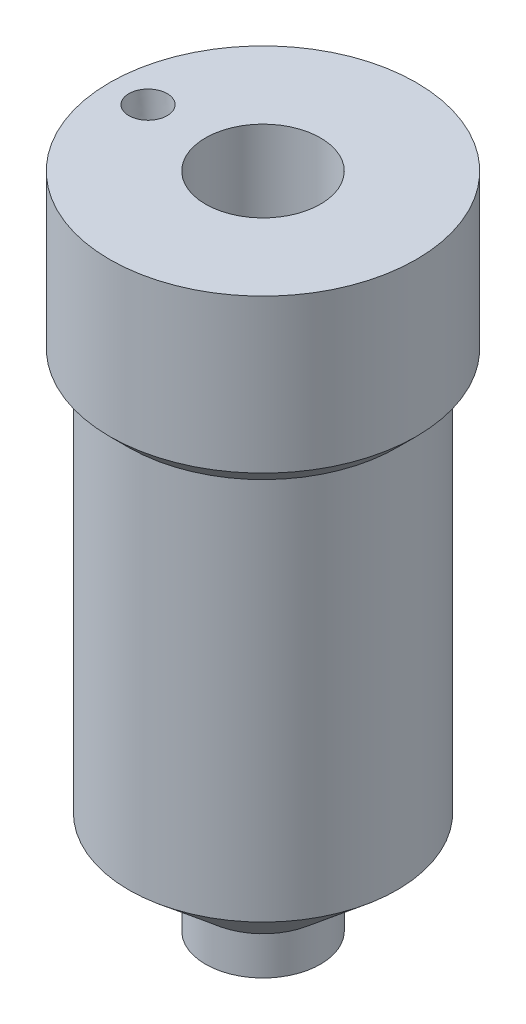
SolidWorks part; units mm, degrees
material "Brass"
ref_plane "Front Plane" through (0, 0, 0) normal (0, 0, 1) x (1, 0, 0)
ref_plane "Top Plane" through (0, 0, 0) normal (0, 1, 0) x (1, 0, 0)
ref_plane "Right Plane" through (0, 0, 0) normal (1, 0, 0) x (0, 0, -1)
sketch "Sketch1" plane through (0, 0, 0) normal (0, 0, 1) x (1, 0, 0)
  line L0 (0, 26.5455) -> (0, -14.7683) construction
  line L1 (3, -1.9686) -> (3, 21.0314)
  line L2 (3, 21.0314) -> (8, 21.0314)
  line L3 (8, 21.0314) -> (8, 13.0314)
  line L4 (8, 13.0314) -> (7, 12.0314)
  line L5 (7, 12.0314) -> (7, -7.9686)
  line L6 (7, -7.9686) -> (3, -11.325)
  line L7 (3, -11.325) -> (3, -13.325)
  line L8 (3, -13.325) -> (0.5, -14.7683)
  line L9 (0.5, -14.7683) -> (0.5, -9.8683)
  line L10 (3, -1.9686) -> (4.9948, -1.9686) construction
  line L11 (0.5, -9.0404) -> (3.9104, -5.6301) construction
  arc A0 (1.0858, -8.4541) -> (0.5, -9.8683) centre (2.5, -9.8683) ccw
  spline S0 degree 3 poles (1.0858, -8.4541) (5.8006, -3.7393) (7.5492, -1.9686) (3, -1.9686) knots 0.037994 0.037994 0.037994 0.037994 1 1 1 1
  point P17 (3, -1.9686)
  dimension "D9" = 2
  dimension "D17" = 13.6475
  dimension "D18" = 20.0031
  dimension "D1" = 8
  dimension "D2" = 3
  dimension "D3" = 7
  dimension "D4" = 0.5
  dimension "D5" = 29
  dimension "D6" = 23
  dimension "D7" = 20
  dimension "D8" = 1
  dimension "D10" = 50
  dimension "D11" = 60
  dimension "D12" = 45
  dimension "D13" = 4.9
  dimension "D14" = 2
  dimension "D15" = 2.5
  dimension "D16" = 14.7683
revolve "Revolve1" add sketch "Sketch1" angle 360 about L0
sketch "Sketch2" plane through (0, 0, 0) normal (0, 0, 1) x (1, 0, 0)
  line L0 (-6, 21.0314) -> (-4.6, -2.9719)
  line L1 (8, 21.0314) -> (-8, 21.0314) construction
  line L2 (3, 21.0314) -> (-3, 21.0314) construction
  point P4 (0, 21.0314)
  dimension "D1" = 6
  dimension "D2" = 24.0034
  dimension "D3" = 4.6
sketch "Sketch3" plane through (0, 21.0314, 0) normal (0, 1, 0) x (1, 0, 0)
  circle A0 centre (-6, 0) radius 1
  dimension "D1" = 2
sweep "Cut-Sweep1" cut profiles "Sketch3" path "Sketch2"
sketch "Sketch4" plane through (0, 0, 0) normal (0, 0, 1) x (1, 0, 0)
  line L0 (0.5, -14.7683) -> (-0.5, -14.7683) construction
  line L1 (0.4, -14.7683) -> (0.5, -14.6683)
  line L2 (0, -14.7683) -> (0.4, -14.7683)
  line L3 (0, -15.1683) -> (0, -15.2683)
  line L4 (0.5, -14.6683) -> (0.5, -14.7683)
  line L5 (0, -14.7683) -> (0, -15.3947) construction
  arc A0 (0, -15.2683) -> (0.5, -14.7683) centre (0, -14.7683) ccw
  arc A1 (0, -15.1683) -> (0.4, -14.7683) centre (0, -14.7683) ccw
  dimension "D1" = 1
  dimension "D2" = 0.8
  dimension "D3" = 0.1
  dimension "D4" = 0.1
revolve "Revolve2" add sketch "Sketch4" angle 360 about L5
sketch "Sketch5" plane through (0, 0, 0) normal (0, 0, 1) x (1, 0, 0)
  line L0 (0, -15.1183) -> (0, -15.4683)
  line L1 (0, -15.4683) -> (0.07, -15.4683)
  line L2 (0.07, -15.4683) -> (0.07, -15.1183)
  line L3 (0.07, -15.1183) -> (0, -15.1183)
  line L4 (0.4, -14.7683) -> (-0.4, -14.7683) construction
  line L5 (-0.1519, -15.0837) -> (-0.3037, -15.399)
  line L6 (-0.0888, -15.114) -> (-0.1519, -15.0837)
  line L7 (-0.2407, -15.4294) -> (-0.0888, -15.114)
  line L8 (-0.3037, -15.399) -> (-0.2407, -15.4294)
  line L9 (-0.2736, -14.9866) -> (-0.5473, -15.2048)
  line L10 (-0.23, -15.0413) -> (-0.2736, -14.9866)
  line L11 (-0.5036, -15.2595) -> (-0.23, -15.0413)
  line L12 (-0.5473, -15.2048) -> (-0.5036, -15.2595)
  line L13 (-0.3412, -14.8462) -> (-0.6824, -14.9241)
  line L14 (-0.3256, -14.9145) -> (-0.3412, -14.8462)
  line L15 (-0.6669, -14.9923) -> (-0.3256, -14.9145)
  line L16 (-0.6824, -14.9241) -> (-0.6669, -14.9923)
  line L57 (-0.698, -14.6808) -> (-0.3568, -14.7587) [skipped]
  line L58 (-0.3412, -14.6904) -> (-0.6824, -14.6126) [skipped]
  line L59 (-0.5909, -14.3866) -> (-0.3173, -14.6048) [skipped]
  line L60 (-0.2736, -14.5501) -> (-0.5473, -14.3319) [skipped]
  line L61 (-0.3668, -14.168) -> (-0.2149, -14.4834) [skipped]
  line L62 (-0.1519, -14.453) -> (-0.3037, -14.1377) [skipped]
  line L63 (-0.07, -14.0683) -> (-0.07, -14.4183) [skipped]
  line L64 (0, -14.4183) -> (0, -14.0683) [skipped]
  line L65 (0.2407, -14.1073) -> (0.0888, -14.4226) [skipped]
  line L66 (0.1519, -14.453) -> (0.3037, -14.1377) [skipped]
  line L67 (0.5036, -14.2772) -> (0.23, -14.4954) [skipped]
  line L68 (0.2736, -14.5501) -> (0.5473, -14.3319) [skipped]
  line L69 (0.6669, -14.5443) -> (0.3256, -14.6222) [skipped]
  line L70 (0.3412, -14.6904) -> (0.6824, -14.6126) [skipped]
  line L71 (0.698, -14.8558) -> (0.3568, -14.778) [skipped]
  line L72 (0.3412, -14.8462) -> (0.6824, -14.9241) [skipped]
  line L73 (0.5909, -15.15) -> (0.3173, -14.9318) [skipped]
  line L74 (0.2736, -14.9866) -> (0.5473, -15.2048) [skipped]
  line L75 (0.3668, -15.3686) -> (0.2149, -15.0533) [skipped]
  line L76 (0.1519, -15.0837) -> (0.3037, -15.399) [skipped]
  line L77 (0.3037, -15.399) -> (0.3668, -15.3686) [skipped]
  line L78 (0.5473, -15.2048) -> (0.5909, -15.15) [skipped]
  line L79 (0.6824, -14.9241) -> (0.698, -14.8558) [skipped]
  line L80 (0.6824, -14.6126) -> (0.6669, -14.5443) [skipped]
  line L81 (0.5473, -14.3319) -> (0.5036, -14.2772) [skipped]
  line L82 (0.3037, -14.1377) -> (0.2407, -14.1073) [skipped]
  line L83 (0, -14.0683) -> (-0.07, -14.0683) [skipped]
  line L84 (-0.3037, -14.1377) -> (-0.3668, -14.168) [skipped]
  line L85 (-0.5473, -14.3319) -> (-0.5909, -14.3866) [skipped]
  line L86 (-0.6824, -14.6126) -> (-0.698, -14.6808) [skipped]
  line L87 (-0.3568, -14.7587) -> (-0.3412, -14.6904) [skipped]
  line L88 (-0.3173, -14.6048) -> (-0.2736, -14.5501) [skipped]
  line L89 (-0.2149, -14.4834) -> (-0.1519, -14.453) [skipped]
  line L90 (-0.07, -14.4183) -> (0, -14.4183) [skipped]
  line L91 (0.0888, -14.4226) -> (0.1519, -14.453) [skipped]
  line L92 (0.23, -14.4954) -> (0.2736, -14.5501) [skipped]
  line L93 (0.3256, -14.6222) -> (0.3412, -14.6904) [skipped]
  line L94 (0.3568, -14.778) -> (0.3412, -14.8462) [skipped]
  line L95 (0.3173, -14.9318) -> (0.2736, -14.9866) [skipped]
  line L96 (0.2149, -15.0533) -> (0.1519, -15.0837) [skipped]
  point P7 (0, -14.7683)
  point P62 (0, -14.7683)
  dimension "D1" = 0.07
  dimension "D2" = 0.35
  dimension "D3" = 0.35
  dimension "D4" = 14
revolve "Cut-Revolve2" cut sketch "Sketch5" angle 360 about L13
sketch "Sketch6" plane through (0, 0, 0) normal (0, 0, 1) x (1, 0, 0)
  line L0 (-0.5473, -15.2048) -> (-0.5036, -15.2595) construction
  line L1 (-0.5036, -15.2595) -> (-0.23, -15.0413) construction
  line L2 (-0.23, -15.0413) -> (-0.2736, -14.9866) construction
  line L3 (-0.2736, -14.9866) -> (-0.5473, -15.2048) construction
  line L4 (-0.5473, -15.2048) -> (-0.5036, -15.2595)
  line L5 (-0.5036, -15.2595) -> (-0.23, -15.0413)
  line L6 (-0.23, -15.0413) -> (-0.2736, -14.9866)
  line L7 (-0.2736, -14.9866) -> (-0.5473, -15.2048)
revolve "Cut-Revolve3" cut sketch "Sketch6" angle 360 about L7
sketch "Sketch7" plane through (0, 0, 0) normal (0, 0, 1) x (1, 0, 0)
  line L0 (-0.3037, -15.399) -> (-0.2407, -15.4294) construction
  line L1 (-0.2407, -15.4294) -> (-0.0888, -15.114) construction
  line L2 (-0.0888, -15.114) -> (-0.1519, -15.0837) construction
  line L3 (-0.1519, -15.0837) -> (-0.3037, -15.399) construction
  line L4 (-0.3037, -15.399) -> (-0.2407, -15.4294)
  line L5 (-0.2407, -15.4294) -> (-0.0888, -15.114)
  line L6 (-0.0888, -15.114) -> (-0.1519, -15.0837)
  line L7 (-0.1519, -15.0837) -> (-0.3037, -15.399)
revolve "Cut-Revolve4" cut sketch "Sketch7" angle 360 about L7
sketch "Sketch8" plane through (0, 0, 0) normal (0, 0, 1) x (1, 0, 0)
  line L0 (0, -15.4683) -> (0.07, -15.4683) construction
  line L1 (0.07, -15.1183) -> (0, -15.1183) construction
  line L2 (0.07, -15.4683) -> (0.07, -15.1183) construction
  line L3 (0, -15.1183) -> (0, -15.4683) construction
  line L4 (0, -15.4683) -> (0.07, -15.4683)
  line L5 (0.07, -15.1183) -> (0, -15.1183)
  line L6 (0.07, -15.4683) -> (0.07, -15.1183)
  line L7 (0, -15.1183) -> (0, -15.4683)
revolve "Cut-Revolve5" cut sketch "Sketch8" angle 360 about L7
ref_axis "Axis2" through (0, -14.6683, 0) along (0, 1, 0)
pattern_circular "CirPattern2" count 14 over 360 about axis through (0, -14.6683, 0) along (0, 1, 0) of "Cut-Revolve2"
pattern_circular "CirPattern3" count 12 over 360 about axis through (0, -14.6683, 0) along (0, 1, 0) of "Cut-Revolve3"
pattern_circular "CirPattern4" count 6 over 360 about axis through (0, -14.6683, 0) along (0, 1, 0) of "Cut-Revolve4"
